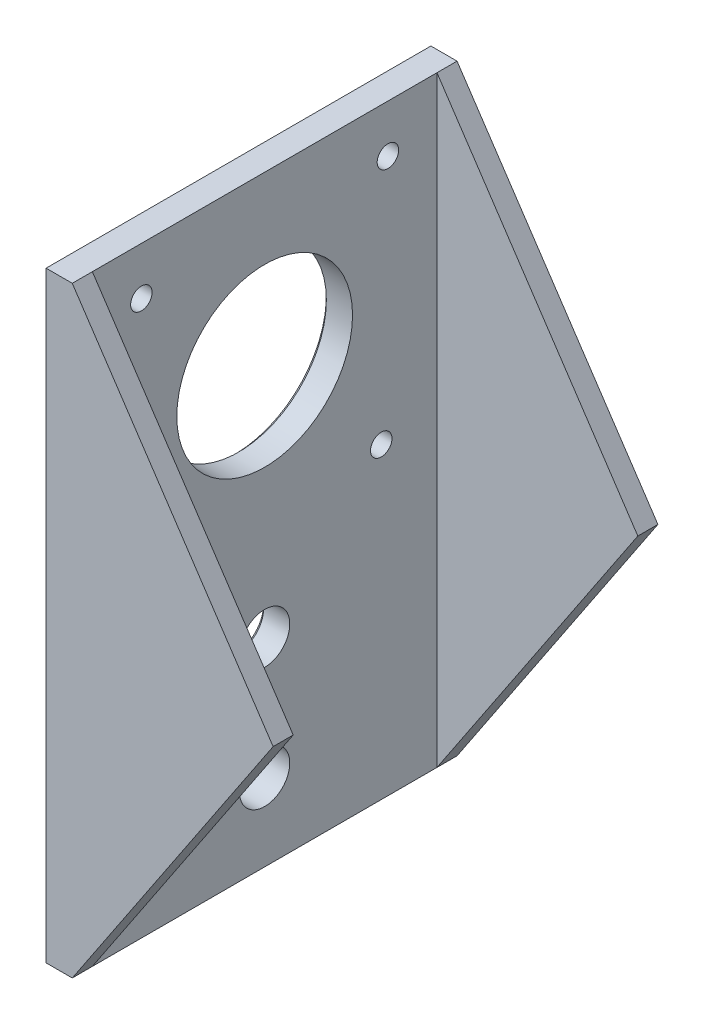
SolidWorks part; units mm, degrees
other "Markup1"
sketch "Sketch7" plane through (-38.1, -21.245, 20.701) normal (-0.7815, -0.4274, 0.4544) x (0.6233, -0.5029, 0.5989)
sketch "Sketch14" plane through (-38.1, -26.289, 21.209) normal (-0.7815, -0.4274, 0.4544) x (0.6233, -0.5029, 0.5989)
sketch "Sketch16" plane through (0, -54.8749, 23.749) normal (-0.7815, -0.4274, 0.4544) x (0.6233, -0.5029, 0.5989)
sketch "Sketch17" plane through (0, -54.8749, 24.13) normal (-0.7815, -0.4274, 0.4544) x (0.6233, -0.5029, 0.5989)
ref_plane "Front Plane" through (0, 0, 0) normal (0, 0, 1) x (1, 0, 0)
ref_plane "Top Plane" through (0, 0, 0) normal (0, 1, 0) x (1, 0, 0)
ref_plane "Right Plane" through (0, 0, 0) normal (1, 0, 0) x (0, 0, -1)
sketch "Sketch1" plane through (0, 0, 0) normal (1, 0, 0) x (0, 0, -1)
  line L0 (21.79, -21.209) -> (21.79, -54.8749)
  line L1 (-21.79, -21.209) -> (21.79, -21.209) construction
  line L2 (-21.79, -21.209) -> (-21.79, 21.209)
  line L3 (-21.79, 21.209) -> (21.79, 21.209)
  line L4 (21.79, -21.209) -> (21.79, 21.209)
  line L5 (-21.79, -21.209) -> (21.79, 21.209) construction
  line L6 (-21.79, 21.209) -> (21.79, -21.209) construction
  line L7 (0, -21.209) -> (0, 21.209) construction
  line L8 (21.79, -54.8749) -> (-21.79, -54.8749)
  line L9 (-21.79, -54.8749) -> (-21.79, -21.209)
  circle A0 centre (0, 0) radius 11.1125
  circle A2 centre (15.5888, 15.1732) radius 1.3589
  circle A6 centre (-15.5888, 15.1732) radius 1.3589
  circle A7 centre (-14.7464, -15.9931) radius 1.3589
  circle A8 centre (14.7464, -15.9931) radius 1.3589
  circle A9 centre (0, -29.845) radius 3.175
  circle A10 centre (0, -45.085) radius 3.175
  point P0 (0, 0)
  dimension "D5" = 22.225
  dimension "D6" = 6.35
  dimension "D1" = 42.418
  dimension "D2" = 43.58
  dimension "D7" = 8.636
  dimension "D8" = 15.24
extrude "Boss-Extrude1" add sketch "Sketch1" along normal blind 3.81
sketch "Sketch15" plane through (0, 0, 21.79) normal (0, 0, 1) x (1, 0, 0)
  line L0 (3.81, 21.209) -> (29.21, -16.833)
  line L1 (29.21, -16.833) -> (3.81, -54.8749)
  line L2 (3.81, -54.8749) -> (0, -54.8749)
  line L3 (0, -54.8749) -> (0, 21.209)
  line L4 (0, 21.209) -> (0, -54.8749) construction
  line L5 (0, 21.209) -> (3.81, 21.209)
  line L6 (3.81, 21.209) -> (3.81, -54.8749) construction
  dimension "D1" = 25.4
extrude "Boss-Extrude2" add sketch "Sketch15" along normal blind 2.54
mirror "Mirror1" about plane through (0, 0, 0) normal (0, 0, 1) of "Boss-Extrude2"
chamfer "Chamfer1" distance 0.5 angle 45 11 edges at (0, -45.085, -3.175) (0, -15.9931, -16.1053) (0, 15.1732, 16.9477) (0, 0, -11.1125) (0, -16.833, 24.33) (0, -54.8749, 0) (0, -16.833, -24.33) (0, 21.209, 0) (0, 15.1732, -16.9477) (0, -15.9931, 16.1053) (0, -29.845, -3.175)
